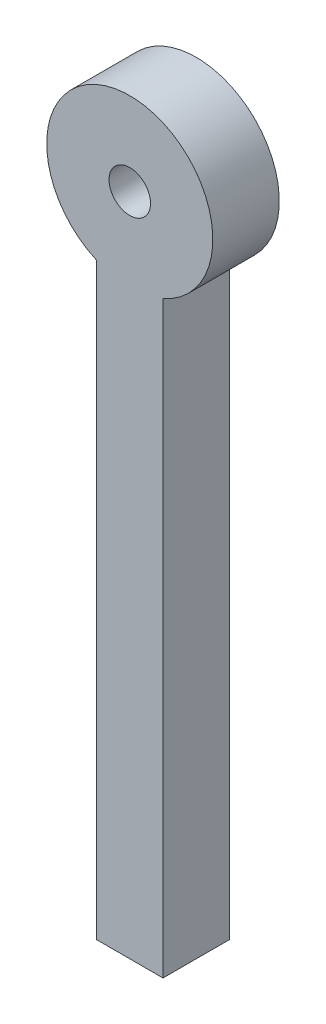
SolidWorks part; units mm, degrees
ref_plane "前视基准面" through (0, 0, 0) normal (0, 0, 1) x (1, 0, 0)
ref_plane "上视基准面" through (0, 0, 0) normal (0, 1, 0) x (1, 0, 0)
ref_plane "右视基准面" through (0, 0, 0) normal (1, 0, 0) x (0, 0, -1)
sketch "草图1" plane through (0, 0, 0) normal (0, 0, 1) x (1, 0, 0)
  line L0 (0, 0) -> (0, -80)
  line L1 (0, -80) -> (4, -80)
  line L2 (0, -80) -> (-4, -80)
  line L3 (4, -80) -> (4, -9.1652)
  line L4 (-4, -80) -> (-4, -9.1652)
  circle A0 centre (0, 0) radius 10
extrude "凸台-拉伸2" add sketch "草图1" along normal blind 8
hole_wizard "M6 螺纹孔1" positions "草图5" profile "草图4" tap size "M6" standard "GB" end condition through all
sketch "草图5" plane through (0, 0, 8) normal (0, 0, 1) x (1, 0, 0)
  point P0 (0, 0)
sketch "草图4" plane through (0, 0, 8) normal (1, 0, 0) x (0, -1, 0)
  line L0 (0, 0) -> (0, 8)
  line L1 (0, 8) -> (2.5, 8)
  line L2 (2.5, 8) -> (2.5, 0)
  line L5 (2.5, 0) -> (0, 0)
  line L11 (0, -6.35) -> (0, 107.95) construction
  dimension "通孔螺纹孔钻头直径" = 5
  dimension "通孔螺纹孔钻头深度" = 8
cosmetic thread "孔螺蚊线1" parameters "D2"=6
